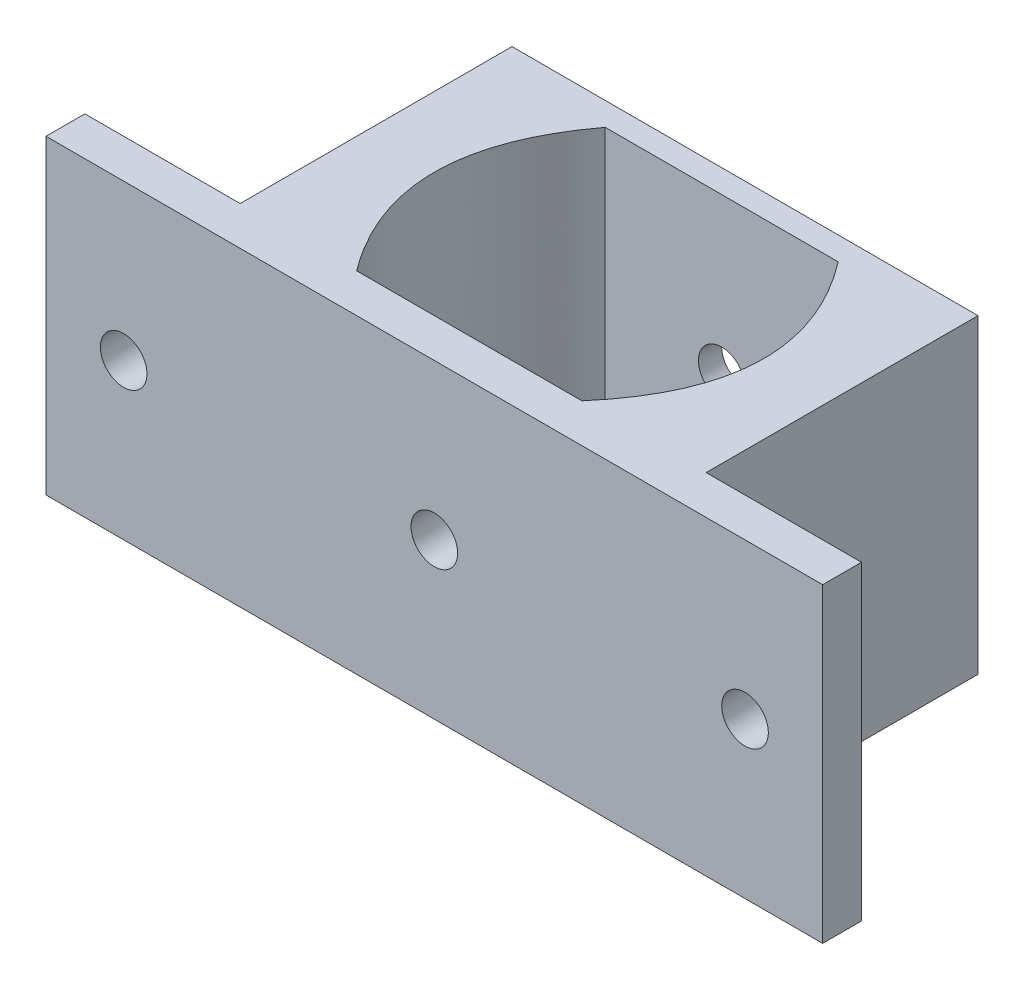
SolidWorks part; units mm, degrees
ref_plane "Front Plane" through (0, 0, 0) normal (0, 0, 1) x (1, 0, 0)
ref_plane "Top Plane" through (0, 0, 0) normal (0, 1, 0) x (1, 0, 0)
ref_plane "Right Plane" through (0, 0, 0) normal (1, 0, 0) x (0, 0, -1)
sketch "Sketch1" plane through (0, 0, 0) normal (0, 1, 0) x (1, 0, 0)
  line L5 (-8.13, 7.5) -> (11.87, 7.5)
  line L8 (-8.13, 7.5) -> (-8.13, -7.5)
  line L9 (11.87, 7.5) -> (11.87, -7.5)
  line L10 (-8.13, 0) -> (-11.13, 0)
  line L11 (11.87, 0) -> (14.87, 0)
  line L12 (-8.13, -7.5) -> (11.87, -7.5)
  line L13 (-8.13, 7.5) -> (-13.13, 7.5)
  line L14 (-13.13, 7.5) -> (-13.13, 10)
  line L15 (11.87, -7.5) -> (16.87, -7.5)
  line L16 (16.87, -7.5) -> (16.87, -10)
  line L18 (-13.13, 10) -> (16.87, 10)
  line L19 (-13.13, 10) -> (-13.13, -10)
  line L20 (-13.13, -10) -> (16.87, -10)
  line L21 (16.87, 10) -> (16.87, -10)
  spline S0 degree 2 poles (-8.13, 7.5) (-14.13, 0) (-8.13, -7.5) knots 0 0 0 1 1 1
  spline S1 degree 2 poles (11.87, 7.5) (17.87, 0) (11.87, -7.5) knots 0 0 0 1 1 1
extrude "Boss-Extrude3" add sketch "Sketch1" along normal blind 20 contours S0 L13 L19 L20 L16 L15 L12 | L5 S1 L15 L21 L18 L14 L13
sketch "Sketch3" plane through (0, 20, 0) normal (0, 1, 0) x (1, 0, 0)
  line L0 (-13.13, -10) -> (-23.13, -10)
  line L1 (-23.13, -7.5) -> (-23.13, -10)
  line L2 (-23.13, -7.5) -> (-13.13, -7.5)
  line L3 (-13.13, 10) -> (-13.13, -10) construction
  line L4 (16.87, -10) -> (26.87, -10)
  line L5 (26.87, -10) -> (26.87, -7.5)
  line L6 (26.87, -7.5) -> (16.87, -7.5)
  line L7 (16.87, 10) -> (16.87, -10) construction
  line L8 (-13.13, -7.5) -> (-13.13, -10)
  line L9 (16.87, -7.5) -> (16.87, -10)
extrude "Boss-Extrude4" add sketch "Sketch3" against normal blind 20 contours L8 L0 L1 L2 | L9 L4 L5 L6
sketch "Sketch4" plane through (0, 0, 7.5) normal (0, 0, -1) x (-1, 0, 0)
  line L0 (23.13, 10) -> (18.13, 10)
  line L1 (23.13, 0) -> (23.13, 20) construction
  line L2 (-26.87, 10) -> (-21.87, 10)
  line L3 (-26.87, 0) -> (-26.87, 20) construction
  circle A0 centre (18.13, 10) radius 1.5
  circle A1 centre (-21.87, 10) radius 1.5
extrude "Cut-Extrude1" cut sketch "Sketch4" against normal blind 3
sketch "Sketch5" plane through (0, 20, 0) normal (0, 1, 0) x (1, 0, 0)
  line L0 (-8.13, 7.5) -> (-8.13, -7.5)
  line L1 (11.87, 7.5) -> (11.87, -7.5)
  line L2 (11.87, -7.5) -> (-8.13, -7.5)
  line L3 (-8.13, 7.5) -> (11.87, 7.5)
  line L4 (-8.13, 7.5) -> (-8.13, -7.5)
  line L5 (11.87, 7.5) -> (11.87, -7.5)
  parabola Q0 (-8.13, 7.5) -> (-8.13, -7.5) focus (-6.4425, 0) apex (-11.13, 0) construction
  parabola Q1 (11.87, 7.5) -> (11.87, -7.5) focus (10.1825, 0) apex (14.87, 0) construction
  spline S0 degree 2 poles (-8.13, 7.5) (-14.13, 0) (-8.13, -7.5) knots 0 0 0 1 1 1
  spline S1 degree 2 poles (11.87, -7.5) (17.87, 0) (11.87, 7.5) knots 0 0 0 1 1 1
  spline M13 degree 2 poles (-8.13, -7.5) (-14.13, 0) (-8.13, 7.5) knots 0 0 0 1 1 1
  spline M15 degree 2 poles (11.87, 7.5) (17.87, 0) (11.87, -7.5) knots 0 0 0 1 1 1
extrude "Boss-Extrude5" add sketch "Sketch5" against normal blind 20 contours L0 M13 | L1 M15
sketch "Sketch6" plane through (0, 20, 0) normal (0, 1, 0) x (1, 0, 0)
  line L0 (-8.13, 7.5) -> (-8.13, 8)
  line L1 (-8.13, 8) -> (11.87, 8)
  line L2 (11.87, 8) -> (11.87, 7.5)
  line L3 (11.87, 7.5) -> (-8.13, 7.5)
extrude "Cut-Extrude2" cut sketch "Sketch6" against normal blind 20
sketch "Sketch8" plane through (0, 20, 0) normal (0, 1, 0) x (1, 0, 0)
  line L0 (-8.13, 8) -> (-5.13, 8)
  line L1 (11.87, 8) -> (-8.13, 8) construction
  line L2 (11.87, 8) -> (8.87, 8)
  line L3 (-8.13, -7.5) -> (-5.13, -7.5)
  line L4 (-8.13, -7.5) -> (11.87, -7.5) construction
  line L5 (11.87, -7.5) -> (8.87, -7.5)
  line L6 (11.87, 8) -> (11.87, -7.5) construction
  line L7 (-8.13, 8) -> (-8.13, -7.5) construction
  line L8 (-8.13, 8) -> (-8.13, -7.5)
  line L9 (11.87, 8) -> (11.87, -7.5)
  spline S0 degree 2 poles (8.87, 8) (14.87, 0.25) (8.87, -7.5) knots 0 0 0 1 1 1
  spline S1 degree 2 poles (-5.13, -7.5) (-11.13, 0.25) (-5.13, 8) knots 0 0 0 1 1 1
  line M1 (-8.13, -7.5) -> (-8.13, 8)
  line M2 (-8.13, 8) -> (11.87, 8)
  line M3 (11.87, 8) -> (11.87, -7.5)
  line M4 (11.87, -7.5) -> (-8.13, -7.5)
extrude "Boss-Extrude11" add sketch "Sketch8" against normal blind 20 contours L8 S1 M2 | S1 M4 M1 | S0 M2 M3 | L9 S0 M4
sketch "Sketch10" plane through (0, 20, 0) normal (0, 1, 0) x (1, 0, 0)
  line L0 (-5.13, 8) -> (-8.13, 8)
  line L1 (11.87, 8) -> (11.87, -7.5)
  line L2 (11.87, -7.5) -> (8.87, -7.5)
  line L3 (-23.13, -10) -> (26.87, -10)
  line L4 (-23.13, -10) -> (-23.13, -7.5)
  line L5 (-23.13, -7.5) -> (26.87, -7.5)
  line L6 (26.87, -10) -> (26.87, -7.5)
  line L7 (-8.13, 8) -> (-8.13, -7.5)
  line L8 (-8.13, -7.5) -> (-5.13, -7.5)
  line L9 (-5.13, -7.5) -> (-5.13, 8)
  line L10 (8.87, 8) -> (11.87, 8)
  line L11 (8.87, -7.5) -> (8.87, 8)
extrude "Cut-Extrude4" cut sketch "Sketch10" against normal blind 20
sketch "Sketch11" plane through (0, 20, 0) normal (0, 1, 0) x (1, 0, 0)
  line L0 (-8.13, 8) -> (-8.13, 8.5)
  line L1 (-8.13, 8.5) -> (11.87, 8.5)
  line L2 (11.87, 8.5) -> (11.87, 8)
  line L3 (11.87, 8) -> (-8.13, 8)
extrude "Cut-Extrude5" cut sketch "Sketch11" against normal blind 20
sketch "Sketch12" plane through (0, 20, 0) normal (0, 1, 0) x (1, 0, 0)
  line L0 (-8.13, 0.5) -> (-5.13, 0.5)
  line L1 (-8.13, 8.5) -> (-8.13, -7.5) construction
  line L2 (-5.13, 0.5) -> (-5.13, 8.5)
  line L4 (11.87, 8.5) -> (-8.13, 8.5) construction
  line L5 (-5.13, 8.5) -> (-5.13, -7.5)
  line L6 (-8.13, -7.5) -> (11.87, -7.5) construction
  line L7 (11.87, 0.5) -> (8.87, 0.5)
  line L8 (11.87, 8.5) -> (11.87, -7.5) construction
  line L9 (8.87, 8.5) -> (8.87, -7.5)
  line L10 (-5.13, 8.5) -> (-8.13, 8.5)
  line L11 (-8.13, 8.5) -> (-8.13, -7.5)
  line L12 (-8.13, -7.5) -> (-5.13, -7.5)
  line L13 (11.87, -7.5) -> (8.87, -7.5)
  line L14 (8.87, 8.5) -> (11.87, 8.5)
  line L15 (11.87, 8.5) -> (11.87, -7.5)
  line L16 (11.87, 8.5) -> (8.87, 8.5)
  line L17 (11.87, -7.5) -> (8.87, -7.5)
  spline S0 degree 2 poles (-5.13, 8.5) (-11.13, 0.5) (-5.13, -7.5) knots 0 0 0 1 1 1
  spline S1 degree 2 poles (8.87, 8.5) (14.87, 0.5) (8.87, -7.5) knots 0 0 0 1 1 1
  line M1 (-8.13, -7.5) -> (-8.13, 8.5)
  line M2 (-8.13, 8.5) -> (11.87, 8.5)
  line M3 (11.87, 8.5) -> (11.87, -7.5)
  line M4 (11.87, -7.5) -> (-8.13, -7.5)
extrude "Boss-Extrude14" add sketch "Sketch12" against normal blind 20 contours S0 M2 M1 | S0 M1 M4 | S1 M3 M4 | S1 M2 M3
sketch "Sketch14" plane through (0, 0, 10) normal (0, 0, 1) x (1, 0, 0)
  line L0 (1.87, 0) -> (1.87, 10)
  line L1 (-23.13, 0) -> (26.87, 0) construction
  line L2 (-23.13, 10) -> (1.87, 10)
  line L3 (-23.13, 0) -> (-23.13, 20) construction
  circle A0 centre (1.87, 10) radius 1.5
extrude "Cut-Extrude9" cut sketch "Sketch14" against normal blind 20 contours L0 A0 L2 | L2 A0 L0
sketch "Sketch15" plane through (0, 20, 0) normal (0, 1, 0) x (1, 0, 0)
  line L0 (-5.13, 8.5) -> (-5.63, 8.5)
  line L1 (-5.13, -7.5) -> (-5.63, -7.5)
  line L2 (-5.13, 8.5) -> (-4.63, 8.5)
  line L3 (8.87, 8.5) -> (-5.13, 8.5) construction
  line L4 (-4.63, 8.5) -> (-4.63, -7.5)
  line L5 (-5.13, -7.5) -> (8.87, -7.5) construction
  line L6 (-4.63, -7.5) -> (-5.13, -7.5)
  parabola Q1 (-5.13, 8.5) -> (-5.13, -7.5) focus (-2.7967, 0.5) apex (-8.13, 0.5) construction
  spline S0 degree 2 poles (-5.63, 8.5) (-10.63, 0.5) (-5.63, -7.5) knots 0 0 0 1 1 1
  spline S1 degree 2 poles (-5.13, 8.5) (-11.13, 0.5) (-5.13, -7.5) knots 0 0 0 1 1 1
  line M5 (-5.13, 8.5) -> (8.87, 8.5)
  line M7 (8.87, -7.5) -> (-5.13, -7.5)
  spline M8 degree 2 poles (-5.13, -7.5) (-11.13, 0.5) (-5.13, 8.5) knots 0 0 0 1 1 1
extrude "Cut-Extrude12" cut sketch "Sketch15" against normal blind 20 contours L0 S0 M8 | S0 L1 M8 | L4 M5 M8 M7
sketch "Sketch17" plane through (0, 20, 0) normal (0, 1, 0) x (1, 0, 0)
  line L0 (8.87, 8.5) -> (8.87, -7.5)
  line L1 (8.87, -7.5) -> (11.87, 0.5)
  line L2 (11.87, 0.5) -> (8.87, 0.5)
  line L3 (-5.63, 8.5) -> (-5.63, -7.5)
  line L4 (-5.63, -7.5) -> (-5.63, 0.5)
  line L5 (-5.63, 0.5) -> (-8.13, 0.5)
  line L6 (-8.13, 0.5) -> (-8.63, 0.5)
  parabola Q0 (8.87, 8.5) -> (8.87, -7.5) focus (6.5366, 0.5) apex (11.87, 0.5) construction
  parabola Q1 (-5.63, 8.5) -> (-5.63, -7.5) focus (-1.73, 0.5) apex (-8.13, 0.5) construction
  spline S0 degree 2 poles (-5.63, 8.5) (-11.63, 0.5) (-5.63, -7.5) knots 0 0 0 1 1 1
  spline M1 degree 2 poles (-5.63, -7.5) (-10.63, 0.5) (-5.63, 8.5) knots 0 0 0 1 1 1
extrude "Cut-Extrude13" cut sketch "Sketch17" against normal blind 20 contours S0 L6 M1 | L6 S0 M1 | L3 L5 M1 | L5 L3 M1
sketch "Sketch18" plane through (0, 20, 0) normal (0, 1, 0) x (1, 0, 0)
  line L0 (8.87, 8.5) -> (8.87, -7.5)
  line L1 (-5.63, 8.5) -> (-5.63, -7.5)
  line L2 (-5.63, -7.5) -> (-5.63, 0.5)
  line L3 (-5.63, 0.5) -> (-8.63, 0.5)
  line L4 (8.87, 8.5) -> (9.37, 8.5)
  line L5 (9.37, 8.5) -> (9.37, -7.5)
  line L6 (9.37, -7.5) -> (8.87, -7.5)
  parabola Q0 (8.87, 8.5) -> (8.87, -7.5) focus (6.5366, 0.5) apex (11.87, 0.5) construction
  parabola Q1 (-5.63, 8.5) -> (-5.63, -7.5) focus (-3.2967, 0.5) apex (-8.63, 0.5) construction
  spline S0 degree 2 poles (8.87, 8.5) (14.87, 0.5) (8.87, -7.5) knots 0 0 0 1 1 1
  spline M5 degree 2 poles (8.87, 8.5) (14.87, 0.5) (8.87, -7.5) knots 0 0 0 1 1 1
extrude "Boss-Extrude16" add sketch "Sketch18" against normal blind 20 contours L5 L0 M5
sketch "Sketch19" plane through (0, 20, 0) normal (0, 1, 0) x (1, 0, 0)
  line L0 (9.37, 7.803) -> (9.37, -6.803)
  parabola Q0 (9.37, 7.803) -> (9.37, -6.803) focus (6.5366, 0.5) apex (11.87, 0.5) construction
  spline S0 degree 2 poles (9.37, 7.803) (14.37, 0.5) (9.37, -6.803) knots 0 0 0 1 1 1
extrude "Boss-Extrude17" add sketch "Sketch19" against normal blind 20
sketch "Sketch20" plane through (0, 20, 0) normal (0, 1, 0) x (1, 0, 0)
  line L0 (8.87, 0.5) -> (11.87, 0.5)
  line L1 (8.87, 8.5) -> (8.87, -7.5) construction
  line L2 (8.87, 8.5) -> (9.37, 8.5)
  line L4 (11.87, 0.5) -> (12.37, 0.5)
  spline S0 degree 2 poles (8.87, 8.5) (14.87, 0.5) (8.87, -7.5) knots 0 0 0 1 1 1
  spline S1 degree 2 poles (9.37, 8.5) (15.6153, 0.3258) (8.87, -7.5) knots 0 0 0 1 1 1
  line M1 (8.87, 8.5) -> (8.87, -7.5)
extrude "Cut-Extrude14" cut sketch "Sketch20" against normal blind 20 contours S0 L0 M1 | S0 L0 M1 | S1 L2 S0 L4 | S1 L4 S0
